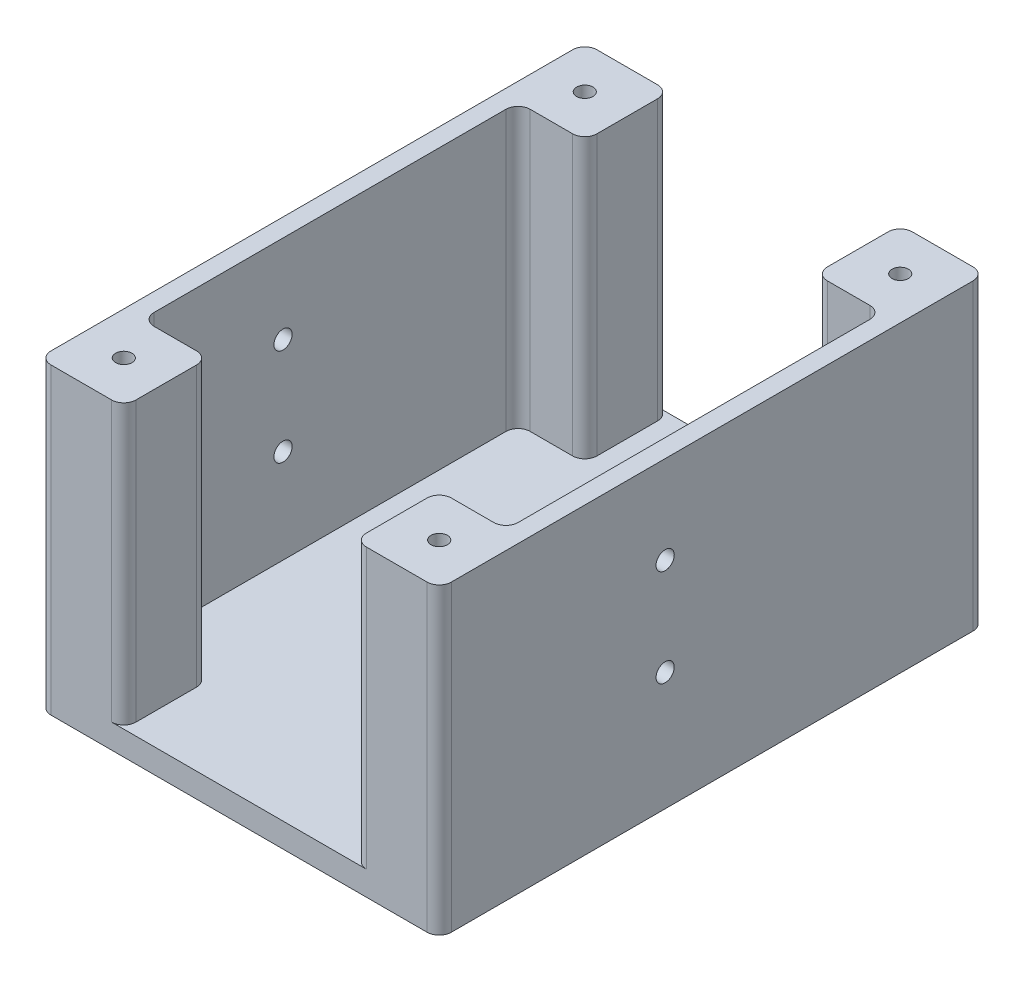
SolidWorks part; units mm, degrees
ref_plane "Front Plane" through (0, 0, 0) normal (0, 0, 1) x (1, 0, 0)
ref_plane "Top Plane" through (0, 0, 0) normal (0, 1, 0) x (1, 0, 0)
ref_plane "Right Plane" through (0, 0, 0) normal (1, 0, 0) x (0, 0, -1)
sketch "Sketch1" plane through (0, 0, 0) normal (0, 1, 0) x (1, 0, 0)
  line L1 (33, -45) -> (-33, -45)
  line L2 (33, -45) -> (33, 45)
  line L3 (33, 45) -> (-33, 45)
  line L4 (-33, -45) -> (-33, 45)
  line L5 (33, -45) -> (-33, 45) construction
  line L6 (33, 45) -> (-33, -45) construction
  point P0 (0, 0)
  dimension "D1" = 66
  dimension "D2" = 90
extrude "Boss-Extrude1" add sketch "Sketch1" along normal blind 50
sketch "Sketch2" plane through (0, 50, 0) normal (0, 1, 0) x (1, 0, 0)
  line L0 (-33, 45) -> (-33, -45) construction
  line L1 (33, 45) -> (-33, 45) construction
  line L2 (0, 0) -> (0, 41.266) construction
  line L3 (0, 0) -> (51.8558, 0) construction
  circle A0 centre (-26, 38) radius 1.35
  circle A1 centre (26, 38) radius 1.35
  circle A2 centre (26, -38) radius 1.35
  circle A3 centre (-26, -38) radius 1.35
  dimension "D1" = 2.7
  dimension "D2" = 7
  dimension "D3" = 7
extrude "Cut-Extrude1" cut sketch "Sketch2" against normal blind 8
sketch "Sketch3" plane through (0, 50, 0) normal (0, 1, 0) x (1, 0, 0)
  line L0 (33, 45) -> (-33, 45) construction
  line L1 (-19, -42) -> (19, -42)
  line L3 (-19, 42) -> (19, 42)
  line L5 (-33, -45) -> (33, -45) construction
  line L6 (-19, 31) -> (-30, 31)
  line L7 (-30, 31) -> (-30, -31)
  line L8 (-30, -31) -> (-19, -31)
  line L9 (-33, 45) -> (-33, -45) construction
  line L10 (-19, -31) -> (-19, -42)
  line L11 (-19, 31) -> (-19, 42)
  line L12 (19, 42) -> (19, 31)
  line L13 (19, 31) -> (30, 31)
  line L14 (30, 31) -> (30, -31)
  line L15 (30, -31) -> (19, -31)
  line L16 (19, -31) -> (19, -42)
  line L17 (33, -45) -> (33, 45) construction
  circle A0 centre (-26, 38) radius 1.35 construction
  circle A2 centre (-26, -38) radius 1.35 construction
  circle A3 centre (26, -38) radius 1.35 construction
  circle A4 centre (26, 38) radius 1.35 construction
  dimension "D1" = 7
  dimension "D2" = 7
  dimension "D3" = 3
  dimension "D4" = 3
  dimension "D5" = 7
  dimension "D6" = 3
  dimension "D7" = 7
  dimension "D8" = 7
  dimension "D9" = 7
  dimension "D10" = 3
  dimension "D11" = 7
  dimension "D12" = 7
extrude "Cut-Extrude2" cut sketch "Sketch3" against normal offset from surface (46 mm away) 4 up to face at (0, 0, 0)
fillet "Fillet1" radius 2 4 edges at (-33, 25, -45) (33, 25, -45) (33, 25, 45) (-33, 25, 45)
sketch "Sketch4" plane through (0, 50, 0) normal (0, 1, 0) x (1, 0, 0)
  line L0 (19, 42) -> (-19, 42) construction
  line L1 (-19, 42) -> (19, 42)
  line L2 (-19, 42) -> (-19, 45)
  line L3 (-19, 45) -> (19, 45)
  line L4 (19, 42) -> (19, 45)
  line L5 (31, 45) -> (-31, 45) construction
  line L6 (-19, 42) -> (-19, 31) construction
  line L7 (19, 31) -> (19, 42) construction
  line L8 (-31, -45) -> (31, -45) construction
  line L9 (-19, -45) -> (19, -45)
  line L10 (-19, -45) -> (-19, -42)
  line L11 (-19, -42) -> (19, -42)
  line L12 (19, -45) -> (19, -42)
  line L13 (-19, -42) -> (19, -42) construction
  line L14 (-19, -31) -> (-19, -42) construction
  line L15 (19, -42) -> (19, -31) construction
  dimension "D1" = 0
  dimension "D2" = 0
  dimension "D3" = 0
  dimension "D4" = 0
extrude "Cut-Extrude3" cut sketch "Sketch4" against normal up to surface (46 mm away) up to face at (0, 4, 0)
fillet "Fillet4" radius 2 12 edges at (30, 27, -31) (19, 27, -31) (19, 27, -45) (-30, 27, -31) (-19, 27, -45) (-19, 27, -31) (-19, 27, 45) (-19, 27, 31) (-30, 27, 31) (19, 27, 45) (19, 27, 31) (30, 27, 31)
sketch "Sketch5" plane through (0, 4, 0) normal (0, 1, 0) x (1, 0, 0)
  line L0 (-30, -29) -> (-30, 29) construction
  line L1 (0, 0) -> (0, 9.8963) construction
  line L2 (0, 0) -> (15.5018, 0) construction
  circle A0 centre (-17.5, 0) radius 1.6
  circle A1 centre (0, 17.5) radius 1.6
  circle A2 centre (0, -17.5) radius 1.6
  circle A3 centre (17.5, 0) radius 1.6
  dimension "D1" = 3.2
  dimension "D2" = 12.5
  dimension "D3" = 17.5
  dimension "D4" = 3.2
  dimension "D5" = 17.5
  dimension "D6" = 30
extrude "Cut-Extrude4" cut sketch "Sketch5" against normal through all
sketch "Sketch6" plane through (0, 4, 0) normal (0, 1, 0) x (1, 0, 0)
  line L1 (-10, -10) -> (10, -10)
  line L2 (-10, -10) -> (-10, 10)
  line L3 (-10, 10) -> (10, 10)
  line L4 (10, -10) -> (10, 10)
  circle A0 centre (0, -17.5) radius 1.6 construction
  circle A1 centre (17.5, 0) radius 1.6 construction
  dimension "D1" = 20
  dimension "D2" = 20
  dimension "D3" = 7.5
  dimension "D4" = 7.5
extrude "Boss-Extrude2" add sketch "Sketch6" along normal blind 3.5
fillet "Fillet5" radius 2 4 edges at (10, 5.75, -10) (-10, 5.75, -10) (10, 5.75, 10) (-10, 5.75, 10)
sketch "Sketch7" plane through (-30, 0, 0) normal (1, 0, 0) x (0, 0, -1)
  line L1 (31, 50) -> (31, 4) construction
  line L2 (8, 7.5) -> (-8, 7.5) construction
  circle A0 centre (-7.75, 19.5) radius 1.5
  circle A1 centre (-7.75, 35.5) radius 1.5
  dimension "D1" = 3
  dimension "D2" = 12
  dimension "D3" = 38.75
  dimension "D4" = 3
  dimension "D5" = 16
  dimension "D6" = 38.75
extrude "Cut-Extrude5" cut sketch "Sketch7" against normal through all both and the other way through all
